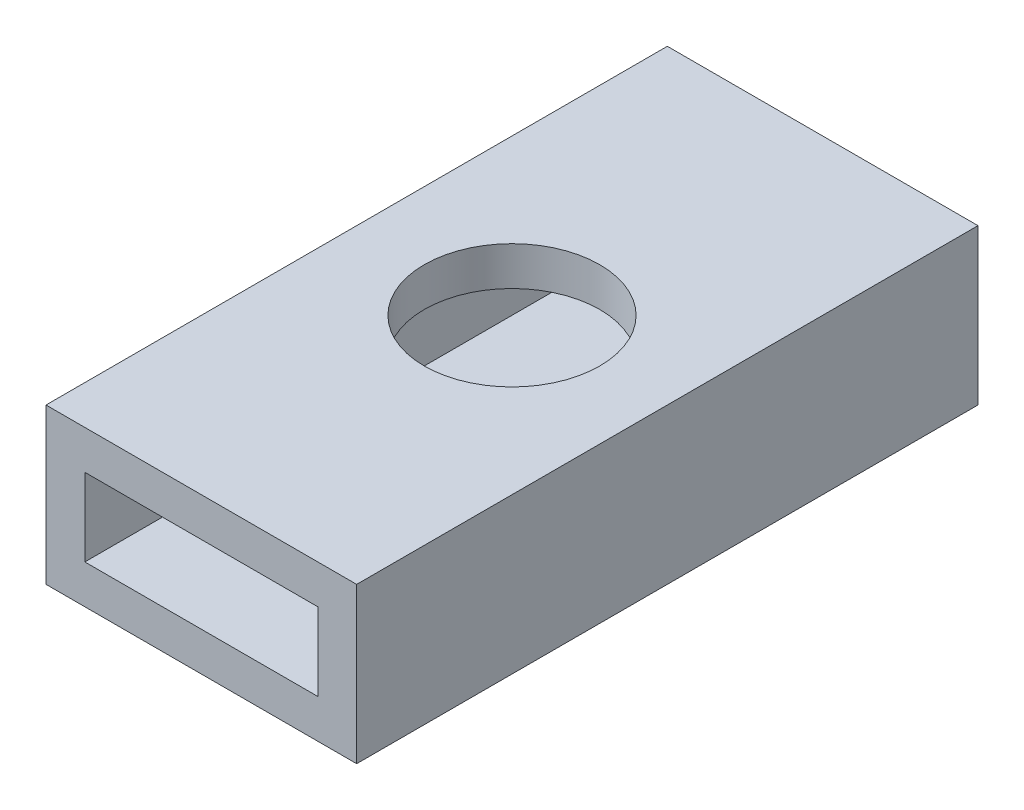
SolidWorks part; units mm, degrees
ref_plane "Front Plane" through (0, 0, 0) normal (0, 0, 1) x (1, 0, 0)
ref_plane "Top Plane" through (0, 0, 0) normal (0, 1, 0) x (1, 0, 0)
ref_plane "Right Plane" through (0, 0, 0) normal (1, 0, 0) x (0, 0, -1)
sketch "Sketch1" plane through (0, 0, 0) normal (0, 0, 1) x (1, 0, 0)
  line L1 (0, 0) -> (50.8, 0)
  line L2 (0, 0) -> (0, 25.4)
  line L3 (0, 25.4) -> (50.8, 25.4)
  line L4 (50.8, 0) -> (50.8, 25.4)
  dimension "D1" = 50.8
  dimension "D2" = 25.4
extrude "Boss-Extrude1" add sketch "Sketch1" along normal blind 101.6
sketch "Sketch2" plane through (0, 0, 101.6) normal (0, 0, 1) x (1, 0, 0)
  line L1 (6.35, 19.05) -> (44.45, 19.05)
  line L2 (6.35, 19.05) -> (6.35, 6.35)
  line L3 (6.35, 6.35) -> (44.45, 6.35)
  line L4 (44.45, 19.05) -> (44.45, 6.35)
  line L9 (50.8, 25.4) -> (0, 25.4) construction
  line L10 (0, 25.4) -> (0, 0) construction
  line L11 (0, 0) -> (50.8, 0) construction
  line L16 (50.8, 0) -> (50.8, 25.4) construction
  dimension "D1" = 6.35
  dimension "D2" = 6.35
  dimension "D3" = 6.35
  dimension "D4" = 6.35
extrude "Cut-Extrude1" cut sketch "Sketch2" against normal through all
sketch "Sketch5" plane through (0, 25.4, 0) normal (0, 1, 0) x (1, 0, 0)
  line L1 (50.8, 0) -> (0, 0) construction
  line L3 (50.8, -101.6) -> (50.8, 0) construction
  circle A0 centre (25.4, -50.8) radius 14.351
  dimension "D1" = 28.702
  dimension "D6" = 25.4
  dimension "D3" = 50.8
extrude "Cut-Extrude3" cut sketch "Sketch5" against normal up to next
